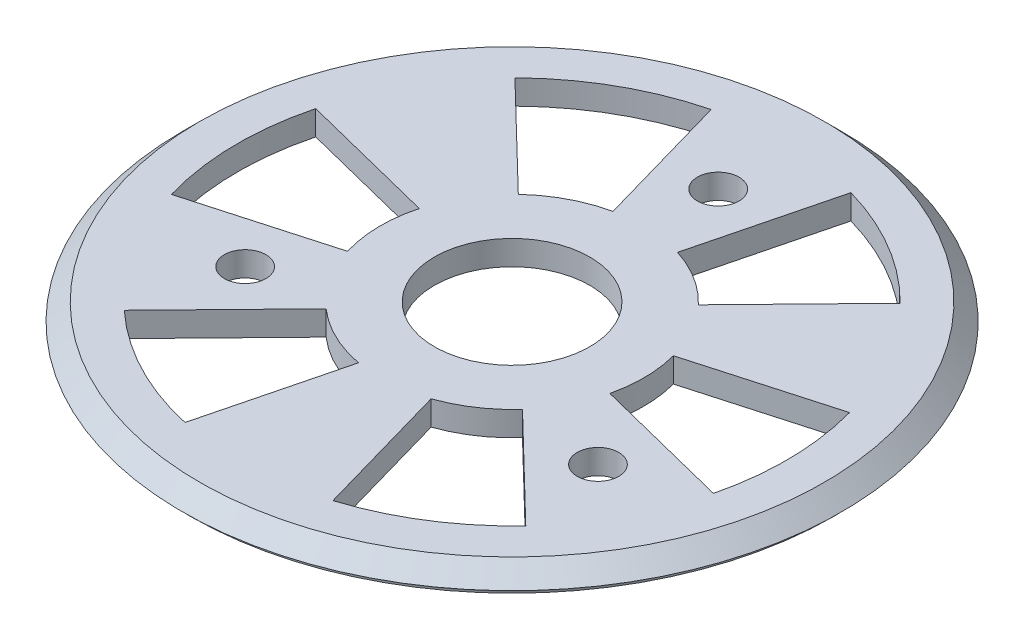
SolidWorks part; units mm, degrees
ref_plane "Front Plane" through (0, 0, 0) normal (0, 0, 1) x (1, 0, 0)
ref_plane "Top Plane" through (0, 0, 0) normal (0, 1, 0) x (1, 0, 0)
ref_plane "Right Plane" through (0, 0, 0) normal (1, 0, 0) x (0, 0, -1)
sketch "Sketch1" plane through (0, 0, 0) normal (0, 0, 1) x (1, 0, 0)
  line L0 (-3, 0) -> (2.8333, 0)
  line L1 (-3, -3) -> (0.175, -3)
  line L2 (-3, -3) -> (-3, 3)
  line L5 (-36.5367, 18.9165) -> (-36.5367, -17.1911)
  line L8 (3.7405, -0.9071) -> (0.175, -3)
  line L9 (3.7405, 0.9071) -> (1.6476, 3)
  line L10 (-3, 3) -> (1.6476, 3)
  arc A0 (3.7405, 0.9071) -> (3.7405, -0.9071) centre (3.7405, 0) ccw
  point P0 (0, 0)
  dimension "D3" = 135
  dimension "D4" = 0.9071
  dimension "D1" = 6
  dimension "D2" = 39.37
revolve "Revolve1" add sketch "Sketch1" angle 360 about L5
sketch "Sketch2" plane through (0, 0, 0) normal (0, 1, 0) x (1, 0, 0)
  line L12 (-20.8677, -3.7179) -> (-3.8352, -7.9993)
  line L13 (-24.5315, -10.7339) -> (-11.9075, -22.9517)
  line L14 (-31.225, -15.2028) -> (-26.4115, -32.107)
  line L15 (-39.4735, -15.8339) -> (-43.7873, -32.8756)
  line L16 (-47.1675, -12.0965) -> (-59.4328, -24.6809)
  line L17 (-51.9399, -4.699) -> (-68.8408, -9.4775)
  line L18 (-52.0809, 4.2089) -> (-69.1149, 8.4873)
  line L19 (-47.5369, 11.7615) -> (-60.1695, 23.9764)
  line L20 (-39.9462, 15.7389) -> (-44.7647, 32.6447)
  line L21 (-31.6677, 15.3503) -> (-27.3586, 32.3904)
  line L22 (-24.8402, 11.0694) -> (-12.5835, 23.6563)
  line L23 (-20.9779, 4.1549) -> (-4.0792, 8.938)
  circle A19 centre (-36.5367, 0) radius 9.5
  arc A20 (-31.225, -15.2028) -> (-24.5315, -10.7339) centre (-36.5367, 0) ccw
  arc A24 (-20.8677, -3.7179) -> (-20.9779, 4.1549) centre (-36.5367, 0) ccw
  arc A25 (-24.8402, 11.0694) -> (-31.6677, 15.3503) centre (-36.5367, 0) ccw
  arc A26 (-39.9462, 15.7389) -> (-47.5369, 11.7615) centre (-36.5367, 0) ccw
  arc A27 (-52.0809, 4.2089) -> (-51.9399, -4.699) centre (-36.5367, 0) ccw
  arc A28 (-47.1675, -12.0965) -> (-39.4735, -15.8339) centre (-36.5367, 0) ccw
  arc A35 (-4.0792, 8.938) -> (-12.5835, 23.6563) centre (-36.5367, 0) ccw
  arc A36 (-27.3586, 32.3904) -> (-44.7647, 32.6447) centre (-36.5367, 0) ccw
  arc A37 (-60.1695, 23.9764) -> (-69.1149, 8.4873) centre (-36.5367, 0) ccw
  arc A38 (-68.8408, -9.4775) -> (-59.4328, -24.6809) centre (-36.5367, 0) ccw
  arc A39 (-43.7873, -32.8756) -> (-26.4115, -32.107) centre (-36.5367, 0) ccw
  arc A40 (-11.9075, -22.9517) -> (-3.8352, -7.9993) centre (-36.5367, 0) ccw
  dimension "D1" = 19
  dimension "D2" = 6.604
extrude "Boss-Extrude1" add sketch "Sketch2" along direction (0, 1, 0) on the side of the normal up to surface (3 mm away) contours L13 A40 L12 A24 L23 A35 L22 A25 L21 A36 L20 A26 L19 A37 L18 A27 L17 A38 L16 A28 L15 A39 L14 A20 | A19
sketch "Sketch3" plane through (0, 3, 0) normal (0, 1, 0) x (1, 0, 0)
  circle A1 centre (-14.4513, 12.5808) radius 2.4765
  circle A3 centre (-35.151, -24.5318) radius 2.4765
  circle A5 centre (-56.9416, 11.951) radius 2.4765
  dimension "D1" = 4.953
  dimension "D3" = 4.953
  dimension "D2" = 4.953
sketch "Sketch5" plane through (0, 3, 0) normal (0, 1, 0) x (1, 0, 0)
  circle A0 centre (-35.8782, 24.5318) radius 2.54
  circle A1 centre (-14.0877, -11.951) radius 2.54
  circle A2 centre (-56.578, -12.5808) radius 2.54
extrude "Boss-Extrude2" add sketch "Sketch3" against normal blind 6 contours A3 | A5 | A1
extrude "Cut-Extrude1" cut sketch "Sketch5" against normal up to surface (3 mm away) up to face at (-16.9278, 0, -12.5808)
